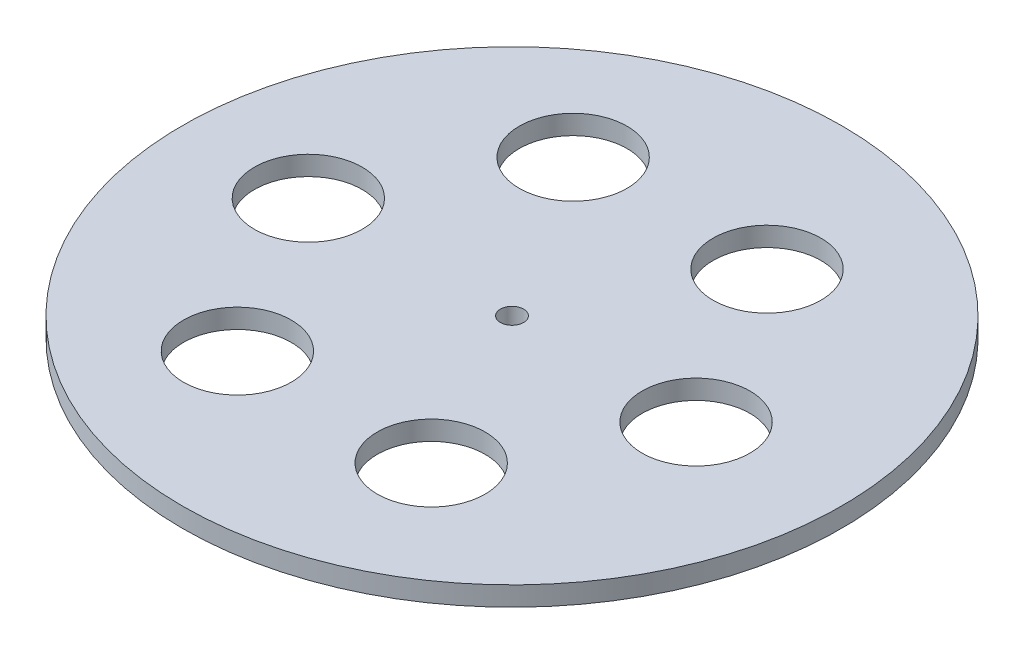
SolidWorks part; units mm, degrees
material "ABS PC"
ref_plane "Front Plane" through (0, 0, 0) normal (0, 0, 1) x (1, 0, 0)
ref_plane "Top Plane" through (0, 0, 0) normal (0, 1, 0) x (1, 0, 0)
ref_plane "Right Plane" through (0, 0, 0) normal (1, 0, 0) x (0, 0, -1)
sketch "Sketch2" plane through (0, 0, 0) normal (0, 1, 0) x (1, 0, 0)
  circle A0 centre (0, 0) radius 85
extrude "Boss-Extrude1" add sketch "Sketch2" along normal blind 5
sketch "Sketch3" plane through (0, 5, 0) normal (0, 1, 0) x (1, 0, 0)
  line L0 (-125.4575, 0) -> (134.5615, 0) construction
  line L1 (0, 92.0392) -> (0, -96.0361) construction
  circle A0 centre (47.4689, 0) radius 13.9011
  circle A1 centre (22.4689, -43.3013) radius 13.9011
  circle A2 centre (-27.5311, -43.3013) radius 13.9011
  circle A3 centre (-52.5311, 0) radius 13.9011
  circle A4 centre (-27.5311, 43.3013) radius 13.9011
  circle A5 centre (22.4689, 43.3013) radius 13.9011
  point P21 (-2.5311, 0)
  dimension "D1" = 6
extrude "Cut-Extrude1" cut sketch "Sketch3" against normal through all
sketch "Sketch4" plane through (0, 5, 0) normal (0, 1, 0) x (1, 0, 0)
  circle A0 centre (0, 0) radius 3
extrude "Cut-Extrude2" cut sketch "Sketch4" against normal blind 10
